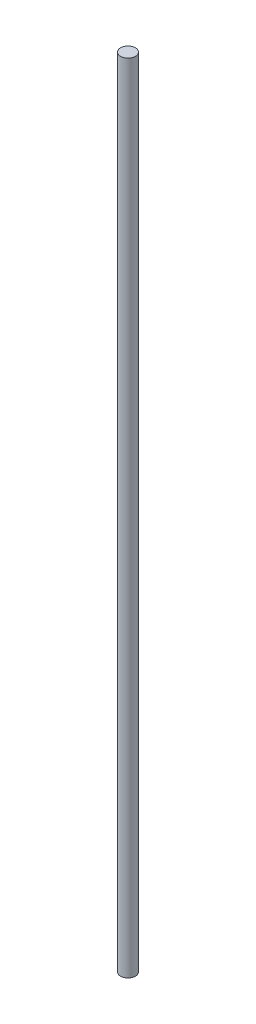
SolidWorks part; units mm, degrees
ref_plane "Front Plane" through (0, 0, 0) normal (0, 0, 1) x (1, 0, 0)
ref_plane "Top Plane" through (0, 0, 0) normal (0, 1, 0) x (1, 0, 0)
ref_plane "Right Plane" through (0, 0, 0) normal (1, 0, 0) x (0, 0, -1)
sketch "Sketch1" plane through (0, 0, 0) normal (0, 1, 0) x (1, 0, 0)
  circle A0 centre (0, 0) radius 4
  dimension "D1" = 8
extrude "Boss-Extrude1" add sketch "Sketch1" along normal blind 430
